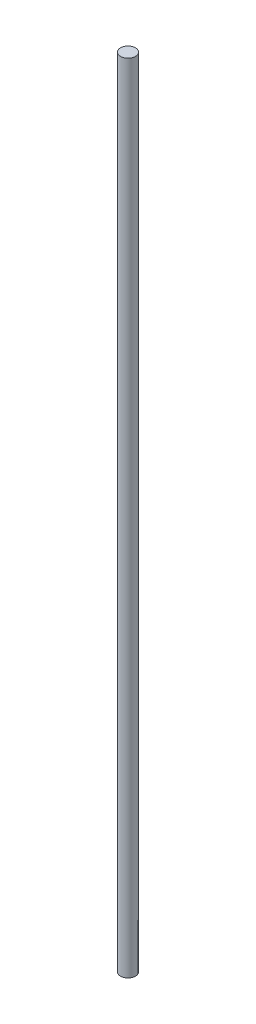
SolidWorks part; units mm, degrees
ref_plane "Front Plane" through (0, 0, 0) normal (0, 0, 1) x (1, 0, 0)
ref_plane "Top Plane" through (0, 0, 0) normal (0, 1, 0) x (1, 0, 0)
ref_plane "Right Plane" through (0, 0, 0) normal (1, 0, 0) x (0, 0, -1)
sketch "Sketch2" plane through (0, 0, 0) normal (0, 1, 0) x (1, 0, 0)
  circle A0 centre (0, 0) radius 4.5
  dimension "D1" = 9
extrude "Boss-Extrude1" add sketch "Sketch2" along normal blind 480
